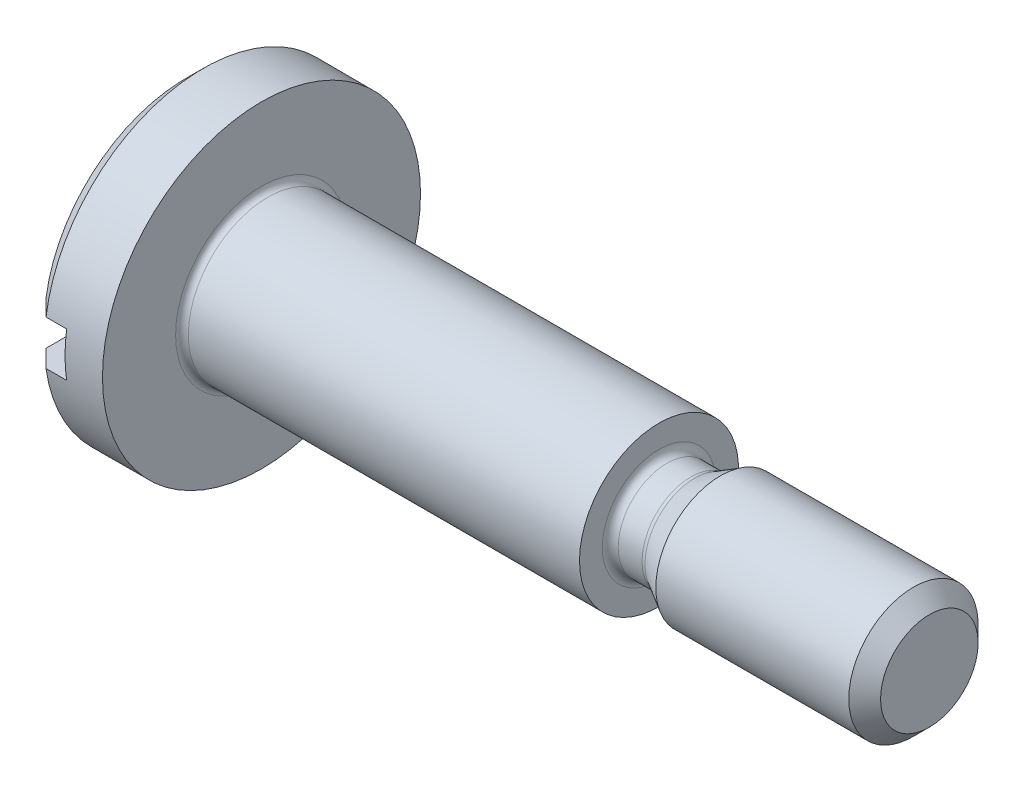
SolidWorks part; units mm, degrees
revolve "Base-Revolve" add sketch "BodySke" angle 360 about L2
sketch "BodySke" plane through (0, 0, 0) normal (0, 0, 1) x (1, 0, 0)
  line L0 (4.75, 5) -> (4.75, 10)
  line L1 (0, 0) -> (0, 8.9)
  line L2 (-25.4, 0) -> (127, 0) construction
  line L3 (46.75, 0) -> (0, 0)
  line L4 (4.75, 5) -> (29.75, 5)
  line L5 (46.75, 3.0663) -> (46.75, 0)
  line L6 (1.1, 10) -> (4.75, 10)
  line L7 (45.75, 4.0663) -> (33.616, 4.0663)
  line L8 (1.1, 10) -> (0, 8.9)
  line L9 (6, 6.5875) -> (6, -2.9375) construction
  line L11 (29.75, 5) -> (29.75, 3.5663)
  line L12 (30.25, 3.0663) -> (31.75, 3.0663)
  line L13 (32, 3.1333) -> (33.616, 4.0663)
  line L14 (46.75, 3.0663) -> (45.75, 4.0663)
  arc A0 (30.25, 3.0663) -> (29.75, 3.5663) centre (30.25, 3.5663) cw
  arc A1 (32, 3.1333) -> (31.75, 3.0663) centre (31.75, 3.5663) cw
  point P6 (46.75, 4.0663)
  dimension "UcutRadius" = 0.5
  dimension "Length" = 25
  dimension "Head_ht" = 4.75
  dimension "Advance" = 1.25
  dimension "Thread_nom" = 17
  dimension "Head_dia" = 20
  dimension "Diameter" = 10
  dimension "D1" = 45
  dimension "Head_chamfer" = 1.1
  dimension "Body_ch_ang" = 45
  dimension "Thread_dia" = 8.1325
  dimension "Thread_nk_ang" = 30
  dimension "Neck" = 2
cosmetic thread "ThreadCosmetic" [suppressed] parameters "Thread_minor"=6.1325
ref_plane "Plane1" through (0, 0, 0) normal (0, 0, 1) x (1, 0, 0)
ref_plane "Plane2" through (0, 0, 0) normal (0, 1, 0) x (1, 0, 0)
ref_plane "Plane3" through (0, 0, 0) normal (1, 0, 0) x (0, 0, -1)
fillet "Fillet1" radius 0.4 1 edges at (4.75, 0, 5)
sketch "Sketch2" plane through (0, 0, 0) normal (1, 0, 0) x (0, 0, -1)
  line L0 (10, -1.4) -> (-10, -1.4)
  line L1 (10, -1.4) -> (10, 1.4)
  line L2 (-10, 1.4) -> (10, 1.4)
  line L3 (-10, 1.4) -> (-10, -1.4)
  line L4 (10, 1.4) -> (-10, -1.4) construction
  dimension "D1" = 20
  dimension "Slot_width" = 2.8
extrude "Slot" cut sketch "Sketch2" along normal blind 2.4
sketch "ThdSchSke" plane through (0, 0, 0) normal (0, 0, 1) x (1, 0, 0)
  line L0 (33, -3.0663) -> (31.646, -5)
  line L1 (33, -3.0663) -> (34.354, -5)
  line L2 (34.354, -5) -> (34.354, -6.25)
  line L3 (-3.175, 0) -> (5.1513, 0) construction
  line L5 (34.354, -6.25) -> (31.646, -6.25)
  line L6 (31.646, -6.25) -> (31.646, -5)
  line L7 (46.75, -5) -> (46.75, 5) construction
  dimension "Diameter" = 10
  dimension "Thread_minor" = 6.1325
  dimension "Start" = 13.75
revolve "ThreadSchematic" [suppressed] cut sketch "ThdSchSke" angle 360 about L3
pattern_linear "ThdSchPat" [suppressed]
equation "\"D1@Sketch2\" = \"Head_dia@BodySke\""
equation "\"Thread_minor@ThreadCosmetic\" = \"Minor_dia@BodySke\""
equation "\"Thread_minor@ThdSchSke\" = \"Minor_dia@BodySke\""
equation "\"Diameter@ThdSchSke\" = \"Diameter@BodySke\""
equation "\"Overcut@ThdSchSke\" = \"Diameter@BodySke\" * 1.25"
equation "\"Start@ThdSchSke\" = \"Thread_nom@BodySke\" - \"Neck@BodySke\" - \"Advance@BodySke\""
equation "\"Num_threads@ThdSchPat\" = int( \"Start@ThdSchSke\" / \"Advance@BodySke\" + 0.999 )  + 1"
equation "\"Advance@ThdSchPat\" = \"Start@ThdSchSke\" /  (\"Num_threads@ThdSchPat\" - 1) 'relax it"
